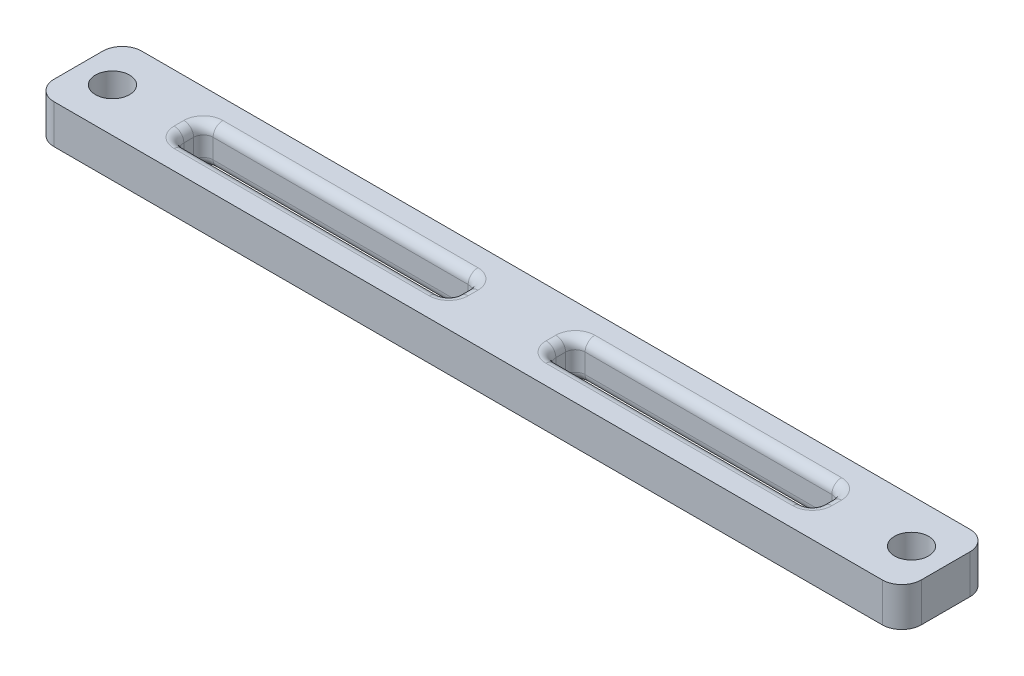
SolidWorks part; units mm, degrees
ref_plane "Front Plane" through (0, 0, 0) normal (0, 0, 1) x (1, 0, 0)
ref_plane "Top Plane" through (0, 0, 0) normal (0, 1, 0) x (1, 0, 0)
ref_plane "Right Plane" through (0, 0, 0) normal (1, 0, 0) x (0, 0, -1)
sketch "Sketch1" plane through (0, 0, 0) normal (0, 1, 0) x (1, 0, 0)
  line L1 (44.5, 4.5) -> (-44.5, 4.5)
  line L2 (44.5, 4.5) -> (44.5, -4.5)
  line L3 (44.5, -4.5) -> (-44.5, -4.5)
  line L4 (-44.5, 4.5) -> (-44.5, -4.5)
  line L5 (44.5, 4.5) -> (-44.5, -4.5) construction
  line L6 (44.5, -4.5) -> (-44.5, 4.5) construction
  point P0 (0, 0)
  dimension "D1" = 89
  dimension "D2" = 9
extrude "Boss-Extrude1" add sketch "Sketch1" along normal blind 4
sketch "Sketch2" plane through (0, 4, 0) normal (0, 1, 0) x (1, 0, 0)
  circle A0 centre (-41, 0) radius 1.75
  circle A1 centre (41, 0) radius 1.75
  dimension "D3" = 3.5
  dimension "D4" = 3.5
  dimension "D1" = 41
  dimension "D2" = 41
extrude "Cut-Extrude1" cut sketch "Sketch2" against normal blind 4
fillet "Fillet1" radius 2 4 edges at (44.5, 2, -4.5) (44.5, 2, 4.5) (-44.5, 2, -4.5) (-44.5, 2, 4.5)
sketch "Sketch4" plane through (0, 4, 0) normal (0, 1, 0) x (1, 0, 0)
  line L0 (42.5, 4.5) -> (-42.5, 4.5) construction
  line L1 (-33.1754, 1.5) -> (-5, 1.5)
  line L2 (-33.1754, 1.5) -> (-33.1754, -1.5)
  line L3 (-33.1754, -1.5) -> (-5, -1.5)
  line L4 (32.3159, 1.5) -> (32.3159, -1.5)
  line L5 (-42.5, -4.5) -> (42.5, -4.5) construction
  line L6 (-5, 1.5) -> (-5, -1.5)
  line L7 (5, 1.5) -> (5, -1.5)
  line L8 (5, 1.5) -> (32.3159, 1.5)
  line L9 (5, -1.5) -> (32.3159, -1.5)
  dimension "D1" = 3
  dimension "D2" = 3
  dimension "D3" = 10
  dimension "D4" = 5
extrude "Cut-Extrude2" cut sketch "Sketch4" against normal through all
fillet "Fillet3" radius 1 24 edges at (-33.1754, 2, 1.5) (-33.1754, 2, -1.5) (18.658, 0, -1.5) (18.658, 4, -1.5) (18.658, 0, 1.5) (18.658, 4, 1.5) (-19.0877, 0, 1.5) (-19.0877, 4, 1.5) (-19.0877, 0, -1.5) (-19.0877, 4, -1.5) (5, 2, -1.5) (5, 2, 1.5) (-5, 2, 1.5) (-5, 2, -1.5) (32.3159, 2, 1.5) (32.3159, 2, -1.5) (32.3159, 0, 0) (32.3159, 4, 0) (-33.1754, 0, 0) (-33.1754, 4, 0) (5, 0, 0) (5, 4, 0) (-5, 0, 0) (-5, 4, 0)
